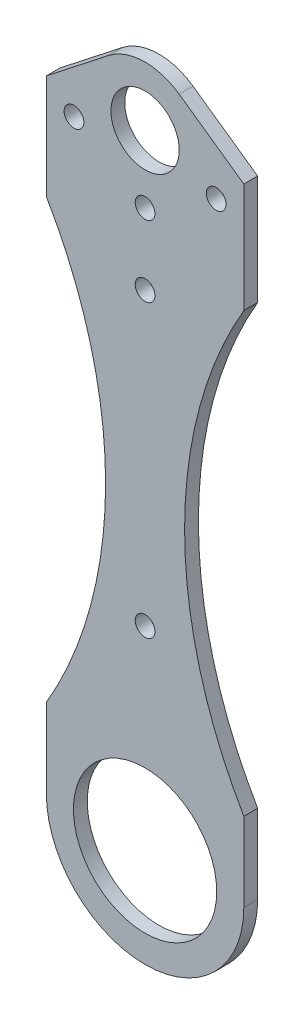
SolidWorks part; units mm, degrees
material "Cedar"
ref_plane "Front Plane" through (0, 0, 0) normal (0, 0, 1) x (1, 0, 0)
ref_plane "Top Plane" through (0, 0, 0) normal (0, 1, 0) x (1, 0, 0)
ref_plane "Right Plane" through (0, 0, 0) normal (1, 0, 0) x (0, 0, -1)
sketch "Sketch2" plane through (0, 0, 0) normal (0, 0, 1) x (1, 0, 0)
  line L0 (0, 112.9665) -> (0, -112.9665) construction
  line L1 (-31.75, 112.9665) -> (31.75, 112.9665)
  line L2 (-31.75, 112.9665) -> (-31.75, -112.9665)
  line L3 (-31.75, -112.9665) -> (31.75, -112.9665)
  line L4 (31.75, 112.9665) -> (31.75, -112.9665)
  line L5 (-31.75, 112.9665) -> (31.75, -112.9665) construction
  line L6 (-31.75, -112.9665) -> (31.75, 112.9665) construction
  line L7 (-31.75, 79.9465) -> (31.75, 79.9465) construction
  arc A0 (-31.75, -112.9665) -> (31.75, -112.9665) centre (0, -112.9665) ccw
  circle A1 centre (0, -112.9665) radius 23.0378
  circle A2 centre (0, 87.5665) radius 10.9855
  circle A3 centre (0, 65.9765) radius 3.175
  circle A4 centre (-22.86, 79.9465) radius 3.175
  circle A5 centre (22.86, 79.9465) radius 3.175
  arc A6 (-31.75, -87.5665) -> (-31.75, 53.2765) centre (-152.3874, -17.145) ccw
  arc A7 (31.75, -87.5665) -> (31.75, 53.2765) centre (152.3874, -17.145) cw
  point P0 (0, 0)
  point P25 (-12.7, -17.145)
  point P26 (12.7, -17.145)
  dimension "D1" = 46.0756
  dimension "D3" = 21.971
  dimension "D4" = 6.35
  dimension "D8" = 6.35
  dimension "D9" = 6.35
  dimension "D13" = 25.4
  dimension "D15" = 25.4
  dimension "D2" = 63.5
  dimension "D5" = 21.59
  dimension "D6" = 13.97
  dimension "D7" = 22.86
  dimension "D10" = 22.86
  dimension "D11" = 200.533
  dimension "D12" = 25.4
  dimension "D14" = 12.7
extrude "Boss-Extrude1" add sketch "Sketch2" along normal blind 4.445 contours L4 A7 L1 L2 A6 L3 A1 A2 A3 A4 A5 | A1 L3 A0
sketch "Sketch4" plane through (0, 0, 4.445) normal (0, 0, 1) x (1, 0, 0)
  line L0 (0, -144.7165) -> (0, 118.8593) construction
  arc A0 (-31.75, -112.9665) -> (31.75, -112.9665) centre (0, -112.9665) ccw construction
  circle A1 centre (0, 43.1165) radius 3.175
  circle A3 centre (0, -50.419) radius 3.175
  circle A4 centre (0, -112.9665) radius 23.0378 construction
  circle A5 centre (0, 87.5665) radius 10.9855 construction
  dimension "D1" = 6.35
  dimension "D2" = 6.35
  dimension "D3" = 44.45
  dimension "D4" = 62.5475
extrude "Cut-Extrude2" cut sketch "Sketch4" against normal through all
sketch "Sketch5" plane through (0, 0, 4.445) normal (0, 0, 1) x (1, 0, 0)
  line L0 (0, -112.9665) -> (0, -89.9287)
  circle A0 centre (0, -112.9665) radius 23.0378 construction
  point P5 (0, 87.5665)
sketch "Sketch6" plane through (0, 0, 0) normal (0, 0, -1) x (-1, 0, 0)
  line L0 (-31.75, 88.5216) -> (-10.9613, 103.147)
  line L1 (-31.75, 112.9665) -> (-31.75, 53.2765) construction
  line L2 (31.75, 86.8882) -> (11.7503, 102.5609)
  line L3 (31.75, 112.9665) -> (31.75, 53.2765) construction
  line L4 (-10.9613, 103.147) -> (-81.5289, 53.5008) construction
  line L5 (11.7503, 102.5609) -> (79.6633, 49.341) construction
  line L6 (-31.75, 88.5216) -> (-31.75, 121.1656)
  line L7 (-31.75, 121.1656) -> (31.75, 121.1656)
  line L8 (31.75, 121.1656) -> (31.75, 86.8882)
  circle A0 centre (0, 87.5665) radius 19.05
  line M12 (31.75, 53.2765) -> (31.75, 112.9665)
  line M13 (31.75, 112.9665) -> (-31.75, 112.9665)
  line M14 (-31.75, 112.9665) -> (-31.75, 53.2765)
extrude "Cut-Extrude3" cut sketch "Sketch6" against normal through all contours A0 L2 L0 M12 M13 M14
